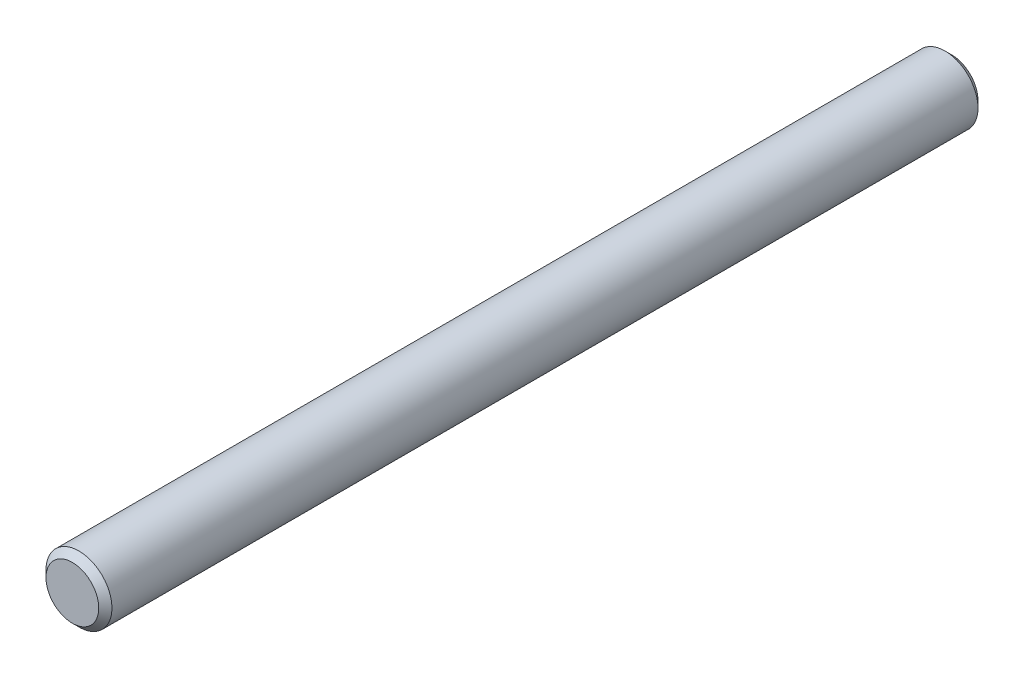
SolidWorks part; units mm, degrees
material "1023 Carbon Steel Sheet (SS)"
ref_plane "Front" through (0, 0, 0) normal (0, 0, 1) x (1, 0, 0)
ref_plane "Top" through (0, 0, 0) normal (0, 1, 0) x (1, 0, 0)
ref_plane "Right" through (0, 0, 0) normal (1, 0, 0) x (0, 0, -1)
sketch "Sketch1" plane through (0, 0, 0) normal (0, 0, 1) x (1, 0, 0)
  circle A0 centre (0, 0) radius 4.7625
  dimension "Diameter" = 9.525
sketch "Sketch2" plane through (0, 0, 0) normal (1, 0, 0) x (0, 0, -1)
  line L0 (-63.5, 0) -> (63.5, 0) construction
  line L1 (-12.7, 4.7625) -> (-12.7, -4.7625) construction
  line L2 (55, 0) -> (-55, 0) construction
  line L3 (12.7, 4.7625) -> (12.7, -4.7625) construction
  line L4 (-63.5, 4.7625) -> (-63.5, -4.7625) construction
  line L5 (63.5, 4.7625) -> (63.5, -4.7625) construction
  point P3 (-12.7, 0)
  point P8 (0, 0)
  point P9 (12.7, 0)
  point P15 (-63.5, 0)
  point P18 (63.5, 0)
  dimension "D1" = 9.525
  dimension "Length" = 127
  dimension "D2" = 50.8
  dimension "D3" = 50.8
sketch "Sketch3" plane through (0, 0, 0) normal (0, 0, 1) x (1, 0, 0)
  circle A0 centre (0, 0) radius 4.7625
  dimension "D1" = 9.525
extrude "Boss-Extrude1" add sketch "Sketch3" along normal mid plane 127
chamfer "Chamfer1" distance 0.9525 angle 45 2 edges at (4.7625, 0, -63.5) (4.7625, 0, 63.5)
equation "\"D1@Sketch3\" = \"Diameter@Sketch1\""
equation "\"D1@Boss-Extrude1\" = \"Length@Sketch2\""
equation "\"D1@Chamfer1\" = \"Diameter@Sketch1\" * .1"
equation "\"D1@Sketch2\" = \"Diameter@Sketch1\""
